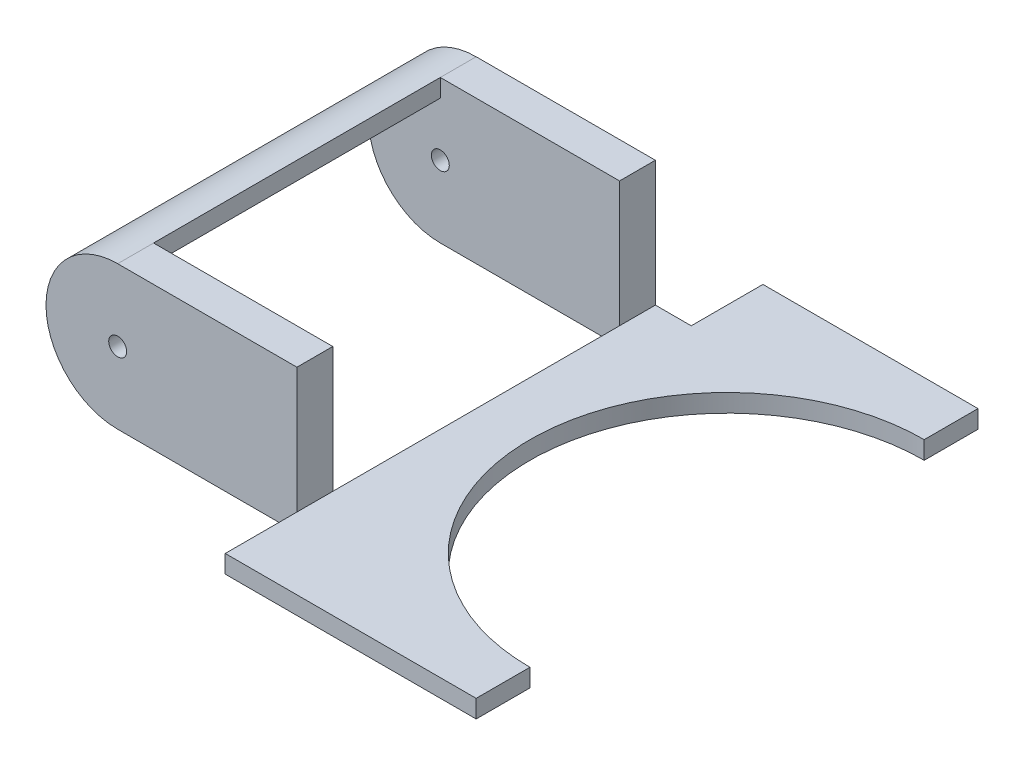
SolidWorks part; units mm, degrees
ref_plane "前视基准面" through (0, 0, 0) normal (0, 0, 1) x (1, 0, 0)
ref_plane "上视基准面" through (0, 0, 0) normal (0, 1, 0) x (1, 0, 0)
ref_plane "右视基准面" through (0, 0, 0) normal (1, 0, 0) x (0, 0, -1)
sketch "草图1" plane through (0, 0, 0) normal (0, 0, 1) x (1, 0, 0)
  line L0 (-50, 0) -> (50, 0) construction
  line L1 (-50, 20) -> (50, 20)
  line L2 (-50, -20) -> (50, -20)
  arc A0 (-50, 20) -> (-50, -20) centre (-50, 0) ccw
  arc A1 (50, -20) -> (50, 20) centre (50, 0) ccw
  point P2 (0, 0)
extrude "凸台-拉伸1" add sketch "草图1" along normal blind 100
sketch "草图2" plane through (0, 0, 100) normal (0, 0, 1) x (1, 0, 0)
  circle A0 centre (-50, 0) radius 2.5
extrude "切除-拉伸1" cut sketch "草图2" against normal through all
sketch "草图3" plane through (0, -20, 0) normal (0, -1, 0) x (1, 0, 0)
  line L0 (0, 100) -> (0, 90)
  line L1 (-50, 100) -> (50, 100) construction
  line L2 (0, 90) -> (-70, 90)
  line L3 (-70, 100) -> (-70, 0) construction
  line L4 (-70, 90) -> (-70, 10)
  line L5 (-70, 10) -> (0, 10)
  line L6 (0, 90) -> (0, 10)
  line M7 (-50, 100) -> (-50, 0)
extrude "切除-拉伸2" cut sketch "草图3" against normal blind 35 contours L4 L5 L2 M7 | L6 L2 L5 M7
sketch "草图4" plane through (0, 20, 0) normal (0, 1, 0) x (1, 0, 0)
  line L0 (0, 0) -> (0, -100)
  line L1 (50, -100) -> (-50, -100) construction
  line L2 (0, -100) -> (70, -100)
  line L3 (70, -100) -> (70, 0)
  line L4 (70, 0) -> (0, 0)
extrude "切除-拉伸3" cut sketch "草图4" against normal blind 35
sketch "草图5" plane through (0, 0, 100) normal (0, 0, 1) x (1, 0, 0)
  line L0 (50, -20) -> (50, -15)
  line L1 (0, -15) -> (63.2288, -15) construction
  line L2 (50, -15) -> (63.2288, -15)
  line L3 (63.2288, -15) -> (63.2288, -20)
  line L4 (63.2288, -20) -> (50, -20)
extrude "切除-拉伸4" cut sketch "草图5" against normal through all
sketch "草图7" plane through (0, -15, 0) normal (0, 1, 0) x (1, 0, 0)
  circle A0 centre (35, -50) radius 2.5
extrude "切除-拉伸5" cut sketch "草图7" against normal through all
sketch "草图8" plane through (0, 20, 0) normal (0, 1, 0) x (1, 0, 0)
  line L1 (-50, -100) -> (-50, 0) construction
  line L2 (-230.551, -90) -> (-57.523, -90) construction
  line L3 (-50, -90) -> (0, -90)
  line L4 (0, 0) -> (0, -100) construction
  line L5 (0, -90) -> (0, -10)
  line L6 (0, -10) -> (-50, -10)
  line L7 (-50, -10) -> (-50, -90)
extrude "切除-拉伸7" cut sketch "草图8" against normal blind 20
sketch "草图10" plane through (0, -15, 0) normal (0, 1, 0) x (1, 0, 0)
  line L0 (50, -100) -> (70, -100)
  line L1 (70, -100) -> (70, 0)
  line L2 (50, -100) -> (50, 0)
  line L3 (50, 0) -> (70, 0)
extrude "凸台-拉伸6" add sketch "草图10" against normal blind 5
sketch "草图11" plane through (0, -20, 0) normal (0, -1, 0) x (-1, 0, 0)
  line L0 (0, -50) -> (-65, -50)
  line L1 (0, -90) -> (0, -10) construction
  line L2 (0, 0) -> (0, 20)
  line L3 (0, 20) -> (-70, 20)
  line L4 (-70, 20) -> (-70, 0)
  line L5 (-70, 0) -> (0, 0)
  line M12 (50, 0) -> (-70, 0)
extrude "凸台-拉伸7" add sketch "草图11" against normal blind 5 contours L3 L4 L2 M12
sketch "草图12" plane through (0, -20, 0) normal (0, -1, 0) x (1, 0, 0)
  line L0 (0, 100) -> (0, 120)
  line L1 (0, 120) -> (70, 120)
  line L2 (70, 120) -> (70, 100)
  line L3 (70, 100) -> (0, 100)
extrude "凸台-拉伸8" add sketch "草图12" against normal blind 5
sketch "草图13" plane through (0, -20, 0) normal (0, -1, 0) x (1, 0, 0)
  line L0 (70, 120) -> (70, -20) construction
  circle A0 centre (70, 50) radius 55
extrude "切除-拉伸8" cut sketch "草图13" against normal blind 5
sketch "草图14" plane through (0, -20, 0) normal (0, -1, 0) x (1, 0, 0)
  line L0 (0, 0) -> (10, 0)
  line L1 (10, 0) -> (10, -20)
  line L2 (0, -20) -> (70, -20) construction
  line L3 (10, -20) -> (0, -20)
  line L4 (0, -20) -> (0, 0)
extrude "切除-拉伸9" cut sketch "草图14" against normal blind 5
